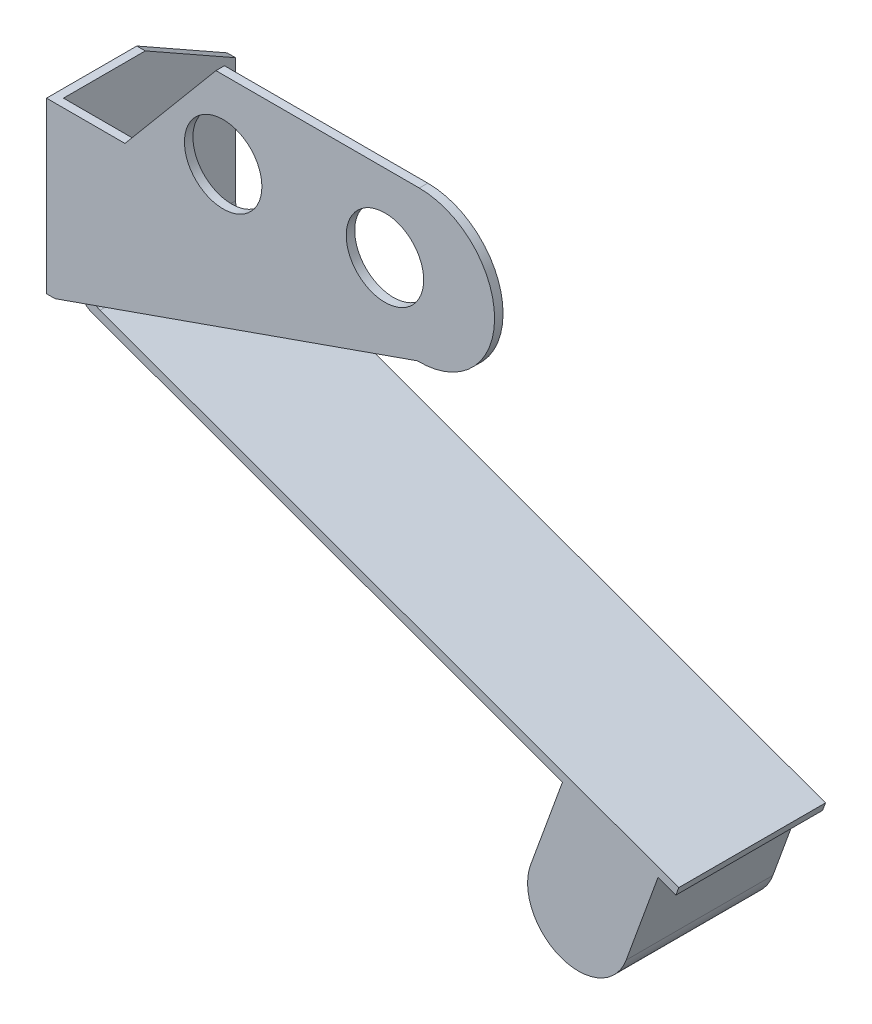
SolidWorks part; units mm, degrees
material "Нержавеющая сталь (ферритная)"
ref_plane "Front" through (0, 0, 0) normal (0, 0, 1) x (1, 0, 0)
ref_plane "Top" through (0, 0, 0) normal (0, 1, 0) x (1, 0, 0)
ref_plane "Right" through (0, 0, 0) normal (1, 0, 0) x (0, 0, -1)
sketch "Эскиз1" plane through (0, 0, 0) normal (0, 0, 1) x (1, 0, 0)
  line L0 (-3.7317, 3.9697) -> (2.2683, 3.9697)
  line L1 (-8.4817, -4.7452) -> (-4.6475, -4.7452) construction
  line L2 (2.2126, -0.4749) -> (-8.4817, -4.2334)
  line L3 (-8.4817, -4.2334) -> (-8.4817, -4.7452)
  line L4 (-8.4817, -4.7452) -> (8.926, -11.0811)
  line L5 (8.926, -11.0811) -> (8.8405, -11.316)
  line L6 (5.4959, -10.0987) -> (-8.7317, -4.9203)
  line L7 (-8.7317, -4.9203) -> (-8.7317, 0.7666)
  line L8 (-8.7317, 0.7666) -> (-6.4163, 0.7666)
  line L9 (-6.4163, 0.7666) -> (-3.7317, 3.9697)
  line L10 (5.4959, -10.0987) -> (4.5554, -12.6828)
  line L11 (8.8405, -11.316) -> (8.315, -11.1248)
  line L12 (7.3745, -13.7089) -> (8.315, -11.1248)
  arc A0 (2.2683, 3.9697) -> (2.2126, -0.4749) centre (2.2683, 1.7471) cw
  arc A1 (4.5554, -12.6828) -> (7.3745, -13.7089) centre (5.9649, -13.1959) ccw
  point P18 (8.315, -11.1248)
  point P21 (8.8666, -11.6747)
  dimension "D10" = 3
  dimension "D11" = 11
  dimension "D1" = 6
  dimension "D2" = 8.89
  dimension "D3" = 0.25
  dimension "D4" = 0.25
  dimension "D5" = 5
  dimension "D6" = 4.445
  dimension "D8" = 20
  dimension "D9" = 18.7
  dimension "D14" = 0.5592
extrude "Бобышка-Вытянуть1" add sketch "Эскиз1" along normal blind 5.33
sketch "Эскиз3" plane through (-2.5173, -6.9161, 0) normal (0.342, 0.9397, 0) x (0.9397, -0.342, 0)
  line L0 (12.1777, -5.33) -> (12.1777, 0) construction
  line L1 (12.1777, -4.33) -> (-6.3473, -4.33)
  line L2 (12.1777, -4.33) -> (12.1777, -5.33)
  line L3 (12.1777, -5.33) -> (-6.3473, -5.33)
  line L4 (-6.3473, -4.33) -> (-6.3473, -5.33)
  dimension "D1" = 1
extrude "Вырез-Вытянуть2" cut sketch "Эскиз3" against normal blind 8
sketch "Эскиз4" plane through (0, 0, 5.33) normal (0, 0, 1) x (1, 0, 0)
  line L0 (2.2683, 3.9697) -> (-3.7317, 3.9697) construction
  line L1 (-8.4817, -4.7452) -> (-8.4817, -4.2334) construction
  circle A0 centre (-3.5193, 1.6837) radius 1.143
  circle A1 centre (1.2559, 1.6837) radius 1.143
  dimension "D1" = 4.7752
  dimension "D2" = 2.286
  dimension "D3" = 2.286
  dimension "D4" = 4.9624
extrude "Вырез-Вытянуть3" cut sketch "Эскиз4" against normal blind 8
sketch "Эскиз5" plane through (0, 3.9697, 0) normal (0, 1, 0) x (1, 0, 0)
  line L0 (-6.4163, 0) -> (-8.7317, 0) construction
  line L1 (-8.4817, 0) -> (6.4248, 0)
  line L2 (-8.4817, 0) -> (-8.4817, -5.08)
  line L3 (-8.4817, -5.08) -> (6.4248, -5.08)
  line L4 (6.4248, 0) -> (6.4248, -5.08)
  line L5 (-8.7317, -5.33) -> (-8.7317, 0) construction
  line L6 (2.2683, -5.33) -> (-3.7317, -5.33) construction
  dimension "D1" = 0.25
  dimension "D2" = 0.25
extrude "Вырез-Вытянуть4" cut sketch "Эскиз5" against normal blind 8.5
fillet "Скругление1" radius 0.5 2 edges at (-8.4817, -4.7452, 2.165) (-8.7317, -4.9203, 2.665)
sketch "Эскиз6" plane through (-8.4817, 0, 0) normal (1, 0, 0) x (0, 0, -1)
  line L0 (-4.33, -11.0811) -> (-4.33, -4.8649) construction
  line L1 (-5.33, -4.2334) -> (-4.33, -4.2334)
  line L2 (-5.33, -4.2334) -> (-5.33, -5.028)
  line L3 (-5.33, -5.028) -> (-4.33, -5.028)
  line L4 (-4.33, -4.2334) -> (-4.33, -5.028)
extrude "Вырез-Вытянуть5" cut sketch "Эскиз6" against normal blind 8.5
sketch "Эскиз7" plane through (-8.7317, 0, 0) normal (-1, 0, 0) x (0, 0, 1)
  line L0 (2.665, 0.7666) -> (0, -0.7402)
  line L1 (5.33, 0.7666) -> (0, 0.7666) construction
  line L2 (0, 0.7666) -> (0, -4.5701) construction
  line L3 (0, -0.7402) -> (0, 0.7666)
  line L4 (0, 0.7666) -> (2.665, 0.7666)
extrude "Вырез-Вытянуть6" cut sketch "Эскиз7" against normal blind 8.5
